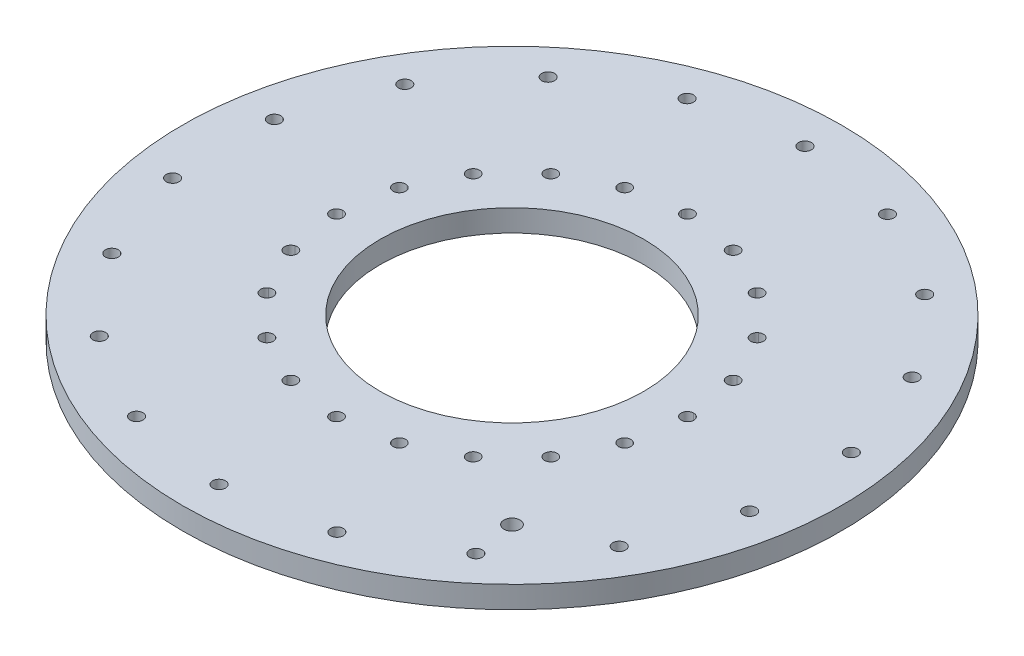
SolidWorks part; units mm, degrees
ref_plane "前视基准面" through (0, 0, 0) normal (0, 0, 1) x (1, 0, 0)
ref_plane "上视基准面" through (0, 0, 0) normal (0, 1, 0) x (1, 0, 0)
ref_plane "右视基准面" through (0, 0, 0) normal (1, 0, 0) x (0, 0, -1)
sketch "草图1" plane through (0, 0, 0) normal (0, 1, 0) x (1, 0, 0)
  circle A0 centre (0, 0) radius 450
extrude "凸台-拉伸1" add sketch "草图1" along normal blind 30
sketch "草图2" plane through (0, 30, 0) normal (0, 1, 0) x (1, 0, 0)
  line L0 (0, 0) -> (0, 239.5) construction
  line L1 (0, -55) -> (0, 55) construction
  line L2 (-55, 0) -> (55, 0) construction
  circle A0 centre (0, 239.5) radius 8.5
  circle A2 centre (74.0096, 227.778) radius 8.5
  circle A3 centre (140.7746, 193.7596) radius 8.5
  circle A4 centre (193.7596, 140.7746) radius 8.5
  circle A5 centre (227.778, 74.0096) radius 8.5
  circle A6 centre (239.5, 0) radius 8.5
  circle A7 centre (227.778, -74.0096) radius 8.5
  circle A8 centre (193.7596, -140.7746) radius 8.5
  circle A9 centre (140.7746, -193.7596) radius 8.5
  circle A10 centre (74.0096, -227.778) radius 8.5
  circle A11 centre (0, -239.5) radius 8.5
  circle A12 centre (-74.0096, -227.778) radius 8.5
  circle A13 centre (-140.7746, -193.7596) radius 8.5
  circle A14 centre (-193.7596, -140.7746) radius 8.5
  circle A15 centre (-227.778, -74.0096) radius 8.5
  circle A16 centre (-239.5, 0) radius 8.5
  circle A17 centre (-227.778, 74.0096) radius 8.5
  circle A18 centre (-193.7596, 140.7746) radius 8.5
  circle A19 centre (-140.7746, 193.7596) radius 8.5
  circle A20 centre (-74.0096, 227.778) radius 8.5
  dimension "D1" = 20
  dimension "D2" = 239.5
extrude "切除-拉伸1" cut sketch "草图2" against normal up to next
ref_plane "基准面1" through (0, 0, 0) normal (-0.7071, 0, 0.7071) x (0, -1, 0)
sketch "草图3" plane through (0, 30, 0) normal (0, 1, 0) x (1, 0, 0)
  circle A0 centre (0, 0) radius 180
extrude "切除-拉伸2" cut sketch "草图3" against normal up to next
sketch "草图7" plane through (0, 0, 0) normal (0, -1, 0) x (1, 0, 0)
  circle A0 centre (239.715, 0) radius 8.5 construction
  circle A1 centre (0, 0) radius 450
  circle A2 centre (0, 0) radius 450 construction
  circle A3 centre (239.715, 0) radius 8.5
  circle A4 centre (227.9825, -74.076) radius 8.5
  circle A5 centre (193.9335, -140.9009) radius 8.5
  circle A6 centre (140.9009, -193.9335) radius 8.5
  circle A7 centre (74.076, -227.9825) radius 8.5
  circle A8 centre (0, -239.715) radius 8.5
  circle A9 centre (-74.076, -227.9825) radius 8.5
  circle A10 centre (-140.9009, -193.9335) radius 8.5
  circle A11 centre (-193.9335, -140.9009) radius 8.5
  circle A12 centre (-227.9825, -74.076) radius 8.5
  circle A13 centre (-239.715, 0) radius 8.5
  circle A14 centre (-227.9825, 74.076) radius 8.5
  circle A15 centre (-193.9335, 140.9009) radius 8.5
  circle A16 centre (-140.9009, 193.9335) radius 8.5
  circle A17 centre (-74.076, 227.9825) radius 8.5
  circle A18 centre (0, 239.715) radius 8.5
  circle A19 centre (74.076, 227.9825) radius 8.5
  circle A20 centre (140.9009, 193.9335) radius 8.5
  circle A21 centre (193.9335, 140.9009) radius 8.5
  circle A22 centre (227.9825, 74.076) radius 8.5
  dimension "D1" = 0
  dimension "D2" = 20
extrude "切除-拉伸5" cut sketch "草图7" against normal up to surface (30 mm away) up to face at (0, 30, 180)
sketch "草图8" plane through (0, 0, 0) normal (0, 1, 0) x (1, 0, 0)
  line L0 (0, 0) -> (74.076, 227.9825) construction
  line L1 (74.076, 227.9825) -> (94.396, 290.5209) construction
  line L5 (-19.626, 374.4861) -> (-18.5793, 354.5135)
  line L6 (18.2744, 374.5545) -> (17.2277, 354.5817)
  line L12 (0, 0) -> (-23.5512, 449.3833) construction
  line L13 (0, 25.8584) -> (22.1996, 449.4521) construction
  line L36 (0, 0) -> (-74.076, 227.9825) construction
  line L38 (0, 0) -> (0, 239.715) construction
  line L39 (0, 239.715) -> (0, 450) construction
  line L40 (0, 0) -> (74.076, 227.9825) construction
  line L41 (140.9009, 193.9335) -> (264.5034, 364.0576) construction
  line L42 (0, 0) -> (140.9009, 193.9335) construction
  line L43 (193.9335, 140.9009) -> (364.0576, 264.5034) construction
  line L44 (0, 0) -> (193.9335, 140.9009) construction
  line L45 (0, 0) -> (227.9825, 74.076) construction
  line L46 (239.715, 0) -> (450, 0) construction
  line L47 (0, 0) -> (239.715, 0) construction
  line L48 (0, 0) -> (227.9825, -74.076) construction
  line L49 (0, 0) -> (193.9335, -140.9009) construction
  line L50 (0, 0) -> (140.9009, -193.9335) construction
  line L51 (0, 0) -> (74.076, -227.9825) construction
  line L52 (0, 0) -> (0, -239.715) construction
  line L53 (0, 0) -> (-74.076, -227.9825) construction
  line L54 (0, 0) -> (-140.9009, -193.9335) construction
  line L55 (0, 0) -> (-227.9825, -74.076) construction
  line L56 (0, 0) -> (-239.715, 0) construction
  line L57 (0, 0) -> (-227.9825, 74.076) construction
  line L58 (0, 0) -> (-193.9335, 140.9009) construction
  line L59 (-193.9335, 140.9009) -> (-364.0576, 264.5034) construction
  line L60 (-227.9825, 74.076) -> (-427.9754, 139.0576) construction
  line L61 (-239.715, 0) -> (-450, 0) construction
  line L62 (-227.9825, -74.076) -> (-427.9754, -139.0576) construction
  line L63 (-193.9335, -140.9009) -> (-364.0576, -264.5034) construction
  line L64 (-140.9009, -193.9335) -> (-264.5034, -364.0576) construction
  line L65 (-74.076, -227.9825) -> (-139.0576, -427.9754) construction
  line L66 (0, -239.715) -> (0, -450) construction
  line L67 (74.076, -227.9825) -> (139.0576, -427.9754) construction
  line L68 (140.9009, -193.9335) -> (264.5034, -364.0576) construction
  line L69 (193.9335, -140.9009) -> (364.0576, -264.5034) construction
  line L70 (227.9825, -74.076) -> (427.9754, -139.0576) construction
  line L71 (0, 0) -> (-193.9335, -140.9009) construction
  line L72 (0, 0) -> (-140.9009, 193.9335) construction
  line L73 (-140.9009, 193.9335) -> (-264.5034, 364.0576) construction
  line L74 (227.9825, 74.076) -> (427.9754, 139.0576) construction
  line L75 (-74.076, 227.9825) -> (-94.396, 290.5209) construction
  circle A2 centre (0, 0) radius 450 construction
  arc A13 (-19.626, 374.4861) -> (18.2744, 374.5545) centre (0, 0) cw
  arc A14 (17.2277, 354.5817) -> (-18.5793, 354.5135) centre (0, 0) ccw
  dimension "D1" = 20
  dimension "D3" = 15
  dimension "D2" = 15
extrude "凸台-拉伸2" [suppressed] add sketch "草图8" against normal blind 40
pattern_circular "阵列(圆周)2" [suppressed] count 4 over 360
sketch "草图9" plane through (0, 0, 0) normal (0, -1, 0) x (1, 0, 0)
  line L0 (0, 0) -> (0, 400) construction
  line L1 (0, -16.5) -> (0, 16.5) construction
  circle A0 centre (0, 400) radius 8.5
  dimension "D1" = 400
extrude "切除-拉伸6" cut sketch "草图9" against normal up to next
pattern_circular "阵列(圆周)3" count 18 over 360 about axis through (0, 0, 0) along (0, 1, 0) of "切除-拉伸6"
sketch "草图10" plane through (0, 0, 0) normal (0, -1, 0) x (1, 0, 0)
  line L1 (0, 0) -> (331.7748, 304.0156) construction
  line L2 (154.7541, 154.7541) -> (-154.7541, -154.7541) construction
  line L3 (253.4691, 276.613) -> (239.9685, 261.8797)
  line L6 (261.8797, 239.9685) -> (276.613, 253.4691)
  arc A0 (261.8797, 239.9685) -> (239.9685, 261.8797) centre (0, 0) ccw
  arc A1 (276.613, 253.4691) -> (253.4691, 276.613) centre (0, 0) ccw
  circle A2 centre (0, 0) radius 450 construction
  dimension "D1" = 2.5
extrude "凸台-拉伸3" [suppressed] add sketch "草图10" along normal blind 40
pattern_circular "阵列(圆周)4" [suppressed] count 4 over 360
sketch "草图11" plane through (0, 30, 0) normal (0, 1, 0) x (1, 0, 0)
  line L0 (258.4446, -246.518) -> (247.4874, -247.4874) construction
  circle A0 centre (247.4874, -247.4874) radius 11 construction
  circle A1 centre (247.4874, -247.4874) radius 11
extrude "切除-拉伸7" cut sketch "草图11" against normal through all
hole_wizard "M16 螺纹孔8" positions "草图12" profile "草图13" tap size "M20" standard "GB" end condition through all
sketch "草图12" plane through (0, 30, 0) normal (0, 1, 0) x (1, 0, 0)
  point P0 (0, -400)
cosmetic thread "孔螺蚊线3" parameters "D1"=24, "D2"=18.5
sketch "草图13" plane through (0, 30, 400) normal (1, 0, 0) x (0, 0, 1)
  line L0 (0, 0) -> (0, 30)
  line L1 (0, 30) -> (8.75, 30)
  line L2 (8.75, 30) -> (8.75, 0)
  line L5 (8.75, 0) -> (0, 0)
  line L11 (0, -6.35) -> (0, 107.95) construction
  dimension "通孔螺纹孔钻头直径" = 17.5
  dimension "通孔螺纹孔钻头深度" = 30
pattern_circular "阵列(圆周)5" count 18 over 360 about axis through (0, 0, 0) along (0, 1, 0) of "M16 螺纹孔8"
